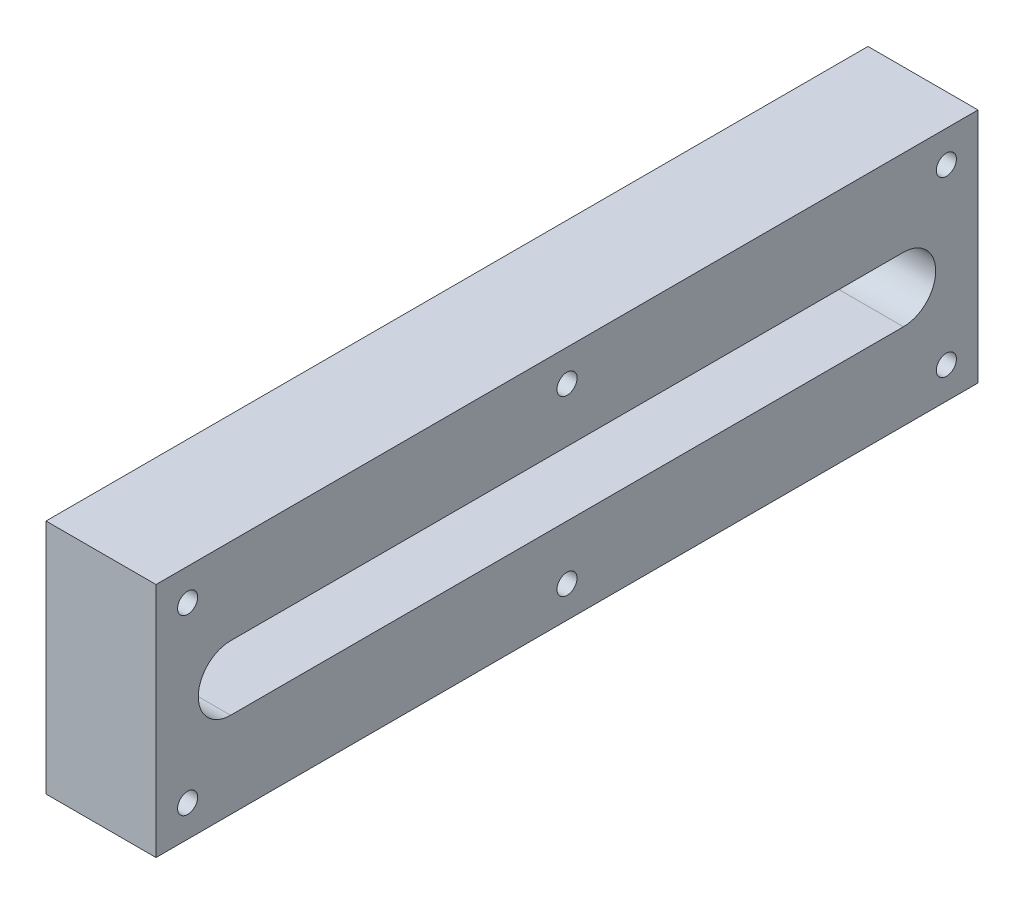
SolidWorks part; units mm, degrees
material "Delrin 2700 NC010, Low Viscosity Acetal Copolymer (SS)"
ref_plane "Front" through (0, 0, 0) normal (0, 0, 1) x (1, 0, 0)
ref_plane "Top" through (0, 0, 0) normal (0, 1, 0) x (1, 0, 0)
ref_plane "Right" through (0, 0, 0) normal (1, 0, 0) x (0, 0, -1)
sketch "Sketch1" plane through (0, 0, 0) normal (1, 0, 0) x (0, 0, -1)
  line L0 (-67.5753, 0) -> (67.5753, 0) construction
  line L1 (82.55, -23.749) -> (-82.55, -23.749)
  line L2 (82.55, -23.749) -> (82.55, 23.749)
  line L3 (82.55, 23.749) -> (-82.55, 23.749)
  line L4 (-82.55, -23.749) -> (-82.55, 23.749)
  line L5 (82.55, -23.749) -> (-82.55, 23.749) construction
  line L6 (82.55, 23.749) -> (-82.55, -23.749) construction
  line L7 (-67.5753, 2.5527) -> (67.5753, 2.5527)
  line L8 (-67.5753, -2.5527) -> (67.5753, -2.5527)
  arc A0 (-67.5753, 2.5527) -> (-67.5753, -2.5527) centre (-67.5753, 0) ccw
  arc A1 (67.5753, -2.5527) -> (67.5753, 2.5527) centre (67.5753, 0) ccw
  point P0 (0, 0)
  point P8 (0, 0)
  dimension "D4" = 5.1054
  dimension "D1" = 135.1505
  dimension "D2" = 165.1
  dimension "D3" = 47.498
extrude "Boss-Extrude1" add sketch "Sketch1" along normal blind 22.098
sketch "Sketch2" plane through (22.098, 0, 0) normal (1, 0, 0) x (0, 0, -1)
  line L0 (-67.5753, 0) -> (67.5753, 0) construction
  line L1 (-67.5753, 6.4798) -> (67.5753, 6.4798)
  line L2 (-67.5753, -6.4798) -> (67.5753, -6.4798)
  line L3 (67.5753, 2.5527) -> (-67.5753, 2.5527) construction
  arc A0 (-67.5753, 6.4798) -> (-67.5753, -6.4798) centre (-67.5753, 0) ccw
  arc A1 (67.5753, -6.4798) -> (67.5753, 6.4798) centre (67.5753, 0) ccw
  point P2 (0, 0)
  dimension "D2" = 12.9595
extrude "Cut-Extrude1" cut sketch "Sketch2" against normal offset from surface (18.249 mm away) 3.849 up to face at (0, 0, 0)
hole_wizard "#10-32 Tapped Hole1" positions "Sketch3" profile "Sketch4" tap size "#10-32" standard "ANSI Inch" end condition through all
sketch "Sketch3" plane through (22.098, 0, 0) normal (1, 0, 0) x (0, 0, -1)
  line L0 (-76.2, 17.399) -> (0, 17.399) construction
  line L1 (0, 17.399) -> (76.2, 17.399) construction
  line L3 (-76.2, 23.749) -> (-76.2, 17.399) construction
  line L4 (82.55, 23.749) -> (-82.55, 23.749) construction
  line L5 (-76.2, 17.399) -> (-76.2, -17.399) construction
  line L6 (-76.2, -17.399) -> (-76.2, -23.749) construction
  line L7 (-82.55, -23.749) -> (82.55, -23.749) construction
  line L8 (-82.55, 23.749) -> (-82.55, -23.749) construction
  point P0 (-76.2, 17.399)
  point P2 (-76.2, -17.399)
  point P4 (0, -17.399)
  point P6 (76.2, -17.399)
  point P8 (76.2, 17.399)
  point P10 (0, 17.399)
  dimension "D1" = 6.35
  dimension "D2" = 6.35
sketch "Sketch4" plane through (22.098, 17.399, 76.2) normal (0, 1, 0) x (0, 0, -1)
  line L0 (0, 0) -> (0, 22.098)
  line L1 (0, 22.098) -> (2.0193, 22.098)
  line L2 (2.0193, 22.098) -> (2.0193, 0)
  line L5 (2.0193, 0) -> (0, 0)
  line L11 (0, -6.35) -> (0, 107.95) construction
  dimension "Thru Tap Drill Dia." = 4.0386
  dimension "Thru Tap Drill Depth" = 22.098
cosmetic thread "Hole Thread1" parameters "D2"=4.826
cosmetic thread "Hole Thread2" parameters "D2"=4.826
cosmetic thread "Hole Thread3" parameters "D2"=4.826
cosmetic thread "Hole Thread4" parameters "D2"=4.826
cosmetic thread "Hole Thread5" parameters "D2"=4.826
cosmetic thread "Hole Thread6" parameters "D2"=4.826
